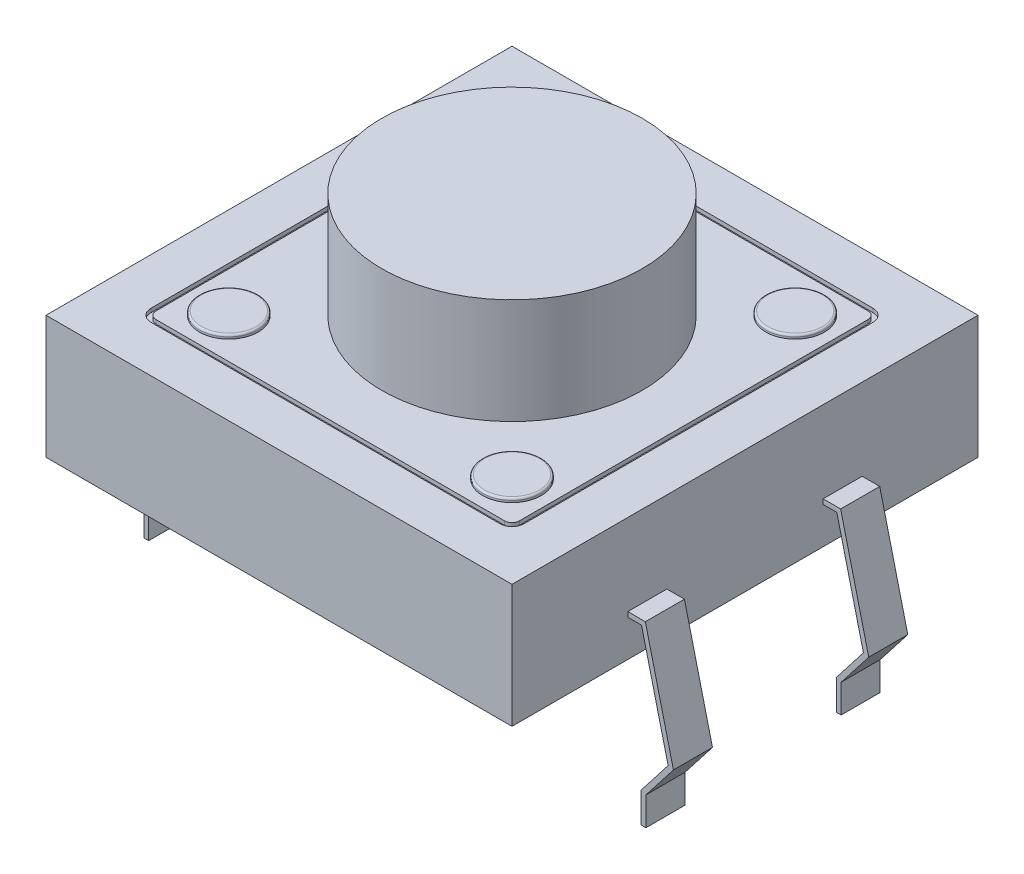
SolidWorks part; units mm, degrees
ref_plane "Front Plane" through (0, 0, 0) normal (0, 0, 1) x (1, 0, 0)
ref_plane "Top Plane" through (0, 0, 0) normal (0, 1, 0) x (1, 0, 0)
ref_plane "Right Plane" through (0, 0, 0) normal (1, 0, 0) x (0, 0, -1)
sketch "Sketch1" plane through (0, 0, 0) normal (0, 1, 0) x (1, 0, 0)
  line L0 (-5.965, 5.965) -> (5.965, -5.965) construction
  line L1 (-5.965, 5.965) -> (5.965, 5.965)
  line L2 (-5.965, 5.965) -> (-5.965, -5.965)
  line L3 (-5.965, -5.965) -> (5.965, -5.965)
  line L4 (5.965, 5.965) -> (5.965, -5.965)
  dimension "D1" = 11.93
extrude "Boss-Extrude1" add sketch "Sketch1" along normal mid plane 3.15
sketch "Sketch2" plane through (0, 1.575, 0) normal (0, 1, 0) x (1, 0, 0)
  line L0 (-4.715, 4.465) -> (-4.715, -4.465)
  line L1 (-4.465, -4.715) -> (4.465, -4.715)
  line L2 (4.715, -4.465) -> (4.715, 4.465)
  line L3 (4.465, 4.715) -> (-4.465, 4.715)
  line L4 (-5.965, 5.965) -> (-5.965, -5.965)
  line L5 (-5.965, -5.965) -> (5.965, -5.965)
  line L6 (5.965, -5.965) -> (5.965, 5.965)
  line L7 (5.965, 5.965) -> (-5.965, 5.965)
  line L8 (-5.965, 5.965) -> (-5.965, -5.965) construction
  line L9 (-5.965, -5.965) -> (5.965, -5.965) construction
  line L10 (5.965, -5.965) -> (5.965, 5.965) construction
  line L11 (5.965, 5.965) -> (-5.965, 5.965) construction
  line L12 (-4.715, 4.715) -> (-4.715, -4.715) construction
  line L13 (4.715, 4.715) -> (-4.715, 4.715) construction
  line L14 (-4.715, -4.715) -> (4.715, -4.715) construction
  line L15 (4.715, -4.715) -> (4.715, 4.715) construction
  arc A0 (-4.715, 4.465) -> (-4.465, 4.715) centre (-4.465, 4.465) cw
  arc A1 (-4.465, -4.715) -> (-4.715, -4.465) centre (-4.465, -4.465) cw
  arc A2 (4.465, -4.715) -> (4.715, -4.465) centre (4.465, -4.465) ccw
  arc A3 (4.715, 4.465) -> (4.465, 4.715) centre (4.465, 4.465) ccw
  dimension "D3" = 0.25
  dimension "D4" = 0.25
  dimension "D5" = 0.25
  dimension "D6" = 0.25
  dimension "D1" = 0
  dimension "D2" = 1.25
extrude "Cut-Extrude-Thin1" cut sketch "Sketch2" against normal blind 0.1 thin thin type mid plane wall 0.125
sketch "Sketch3" plane through (0, 1.575, 0) normal (0, 1, 0) x (1, 0, 0)
  line L0 (-3.625, 3.625) -> (3.625, -3.625) construction
  line L1 (-3.625, 3.625) -> (3.625, 3.625) construction
  line L2 (-3.625, 3.625) -> (-3.625, -3.625) construction
  line L3 (-3.625, -3.625) -> (3.625, -3.625) construction
  line L4 (3.625, 3.625) -> (3.625, -3.625) construction
  circle A0 centre (-3.625, 3.625) radius 0.75
  circle A1 centre (3.625, 3.625) radius 0.75
  circle A2 centre (3.625, -3.625) radius 0.75
  circle A3 centre (-3.625, -3.625) radius 0.75
  dimension "D1" = 1.5
  dimension "D2" = 7.25
extrude "Boss-Extrude2" add sketch "Sketch3" along normal blind 0.1
fillet "Fillet1" radius 0.05 4 edges at (3.625, 1.675, -2.875) (3.625, 1.675, 4.375) (-3.625, 1.675, 4.375) (-3.625, 1.675, -2.875)
sketch "Sketch4" plane through (0, 1.575, 0) normal (0, 1, 0) x (1, 0, 0)
  circle A0 centre (0, 0) radius 3.335
  dimension "D1" = 6.67
extrude "Boss-Extrude3" add sketch "Sketch4" along normal blind 2.7
sketch "Sketch5" plane through (0, 0, 5.965) normal (0, 0, 1) x (1, 0, 0)
  line L0 (0, 0) -> (0, -3.1591) construction
  line L1 (-6.365, -0.575) -> (6.365, -0.575)
  line L2 (6.365, -0.575) -> (7.065, -3.425)
  line L3 (7.065, -3.425) -> (6.365, -4.325)
  line L4 (6.365, -4.325) -> (6.365, -5.075)
  line L5 (-5.965, -1.575) -> (5.965, -1.575) construction
  line L6 (5.965, 1.575) -> (5.965, -1.575) construction
  line L7 (-6.365, -4.325) -> (-6.365, -5.075)
  line L8 (-7.065, -3.425) -> (-6.365, -4.325)
  line L9 (-6.365, -0.575) -> (-7.065, -3.425)
  point P12 (0, 0)
  point P13 (6.365, -3.7409)
  point P14 (6.365, -0.575)
  point P15 (6.365, -0.575)
  point P16 (7.065, -2.5944)
  point P17 (6.365, -4.3228)
  point P22 (0, -0.575)
  dimension "D1" = 3.5
  dimension "D2" = 1.1
  dimension "D3" = 0.4
  dimension "D4" = 1
  dimension "D5" = 1.85
  dimension "D6" = 0.9
extrude "Extrude-Thin1" add sketch "Sketch5" against normal blind 11.92 thin thin type mid plane wall 0.125
sketch "Sketch6" plane through (5.965, 0, 0) normal (1, 0, 0) x (0, 0, -1)
  line L0 (0, 0) -> (0, -2.7925) construction
  line L1 (2, -5.6008) -> (-2, -5.6008)
  line L2 (2, -5.6008) -> (2, 2.1251)
  line L3 (2, 2.1251) -> (-2, 2.1251)
  line L4 (-2, -5.6008) -> (-2, 2.1251)
  line L5 (-7.75, 2.1251) -> (-3, 2.1251)
  line L6 (-7.75, 2.1251) -> (-7.75, -5.6008)
  line L7 (-7.75, -5.6008) -> (-3, -5.6008)
  line L8 (-3, 2.1251) -> (-3, -5.6008)
  line L9 (3, 2.1251) -> (3, -5.6008)
  line L10 (7.75, -5.6008) -> (3, -5.6008)
  line L11 (7.75, 2.1251) -> (7.75, -5.6008)
  line L12 (7.75, 2.1251) -> (3, 2.1251)
  line L13 (-2, -1.1141) -> (2, -1.1141) construction
  point P15 (0, -1.1141)
  point P16 (-7.75, -0.4181)
  point P18 (-7.1715, 2.1251)
  point P20 (0, 0)
  point P21 (2.7051, 2.1251)
  dimension "D1" = 1
  dimension "D2" = 4
extrude "Cut-Extrude1" cut sketch "Sketch6" along normal through all contours L4 L3 L2 L1 | L6 L5 L8 L7 | L9 L10 L11 L12
sketch "Sketch7" plane through (-5.965, 0, 0) normal (-1, 0, 0) x (0, 0, 1)
  line L4 (-3, -5.6008) -> (-3, 2.1251)
  line L5 (-7.75, -5.6008) -> (-3, -5.6008)
  line L6 (-7.75, 2.1251) -> (-7.75, -5.6008)
  line L7 (-3, 2.1251) -> (-7.75, 2.1251)
  line L8 (-3, -5.6008) -> (-3, 2.1251)
  line L9 (-7.75, -5.6008) -> (-3, -5.6008)
  line L10 (-7.75, 2.1251) -> (-7.75, -5.6008)
  line L11 (-3, 2.1251) -> (-7.75, 2.1251)
  line L12 (7.75, 2.1251) -> (3, 2.1251)
  line L13 (3, 2.1251) -> (3, -5.6008)
  line L14 (3, -5.6008) -> (7.75, -5.6008)
  line L15 (7.75, -5.6008) -> (7.75, 2.1251)
  line L16 (7.75, 2.1251) -> (3, 2.1251)
  line L17 (3, 2.1251) -> (3, -5.6008)
  line L18 (3, -5.6008) -> (7.75, -5.6008)
  line L19 (7.75, -5.6008) -> (7.75, 2.1251)
  line L20 (-2, -5.6008) -> (2, -5.6008)
  line L21 (2, -5.6008) -> (2, 2.1251)
  line L22 (2, 2.1251) -> (-2, 2.1251)
  line L23 (-2, 2.1251) -> (-2, -5.6008)
  line L24 (-2, -5.6008) -> (2, -5.6008)
  line L25 (2, -5.6008) -> (2, 2.1251)
  line L26 (2, 2.1251) -> (-2, 2.1251)
  line L27 (-2, 2.1251) -> (-2, -5.6008)
  dimension "D1" = 0
  dimension "D2" = 0
  dimension "D3" = 0
extrude "Cut-Extrude2" cut sketch "Sketch7" along normal through all
